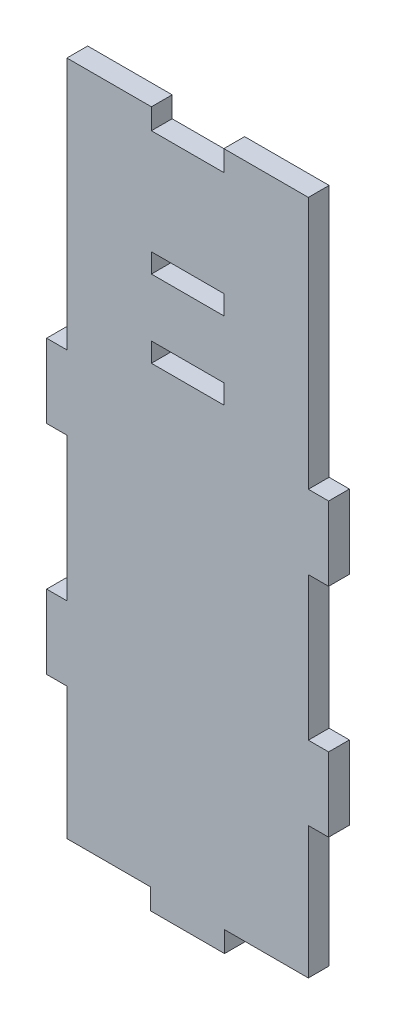
SolidWorks part; units mm, degrees
ref_plane "Front Plane" through (0, 0, 0) normal (0, 0, 1) x (1, 0, 0)
ref_plane "Top Plane" through (0, 0, 0) normal (0, 1, 0) x (1, 0, 0)
ref_plane "Right Plane" through (0, 0, 0) normal (1, 0, 0) x (0, 0, -1)
sketch "Sketch1" plane through (0, 0, 0) normal (0, 0, 1) x (1, 0, 0)
  line L0 (25, -27.35) -> (25, 2.35)
  line L1 (-25, -70) -> (-7.65, -70)
  line L2 (-25, -70) -> (-25, -42.65)
  line L3 (-25, 70) -> (-7.5, 70)
  line L4 (25, -70) -> (25, -42.65)
  line L5 (-25, -70) -> (25, 70) construction
  line L6 (-25, 70) -> (25, -70) construction
  line L7 (25, -42.65) -> (29.2, -42.65)
  line L9 (25, -27.35) -> (29.2, -27.35)
  line L10 (29.2, -42.65) -> (29.2, -27.35)
  line L11 (25, 2.35) -> (29.2, 2.35)
  line L13 (25, 17.65) -> (29.2, 17.65)
  line L14 (29.2, 2.35) -> (29.2, 17.65)
  line L15 (25, 17.65) -> (25, 70)
  line L16 (0, 65.7) -> (0, -74.3) construction
  line L17 (-29.2, 2.35) -> (-29.2, 17.65)
  line L18 (-25, 17.65) -> (-29.2, 17.65)
  line L19 (-25, 2.35) -> (-29.2, 2.35)
  line L20 (-29.2, -42.65) -> (-29.2, -27.35)
  line L21 (-25, -27.35) -> (-29.2, -27.35)
  line L22 (-25, -42.65) -> (-29.2, -42.65)
  line L23 (-25, 17.65) -> (-25, 70)
  line L24 (-25, -27.35) -> (-25, 2.35)
  line L25 (7.5, 70) -> (25, 70)
  line L27 (-7.5, 70) -> (-7.5, 65.7)
  line L28 (-7.5, 65.7) -> (7.5, 65.7)
  line L29 (7.5, 70) -> (7.5, 65.7)
  line L30 (7.65, -70) -> (25, -70)
  line L32 (-7.65, -70) -> (-7.65, -74.3)
  line L33 (-7.65, -74.3) -> (7.65, -74.3)
  line L34 (7.65, -70) -> (7.65, -74.3)
  line L36 (-7.5, 24) -> (7.5, 24)
  line L37 (-7.5, 24) -> (-7.5, 28)
  line L38 (-7.5, 28) -> (7.5, 28)
  line L39 (7.5, 24) -> (7.5, 28)
  line L40 (-7.5, 24) -> (7.5, 28) construction
  line L41 (-7.5, 28) -> (7.5, 24) construction
  line L42 (-7.5, 44) -> (7.5, 44)
  line L43 (-7.5, 44) -> (-7.5, 40)
  line L44 (-7.5, 40) -> (7.5, 40)
  line L45 (7.5, 44) -> (7.5, 40)
  line L46 (-7.5, 44) -> (7.5, 40) construction
  line L47 (-7.5, 40) -> (7.5, 44) construction
  point P0 (0, 0)
  point P16 (29.2, -35)
  point P17 (29.2, 10)
  point P30 (0, -74.3)
  point P31 (0, 42)
  point P32 (0, 65.7)
  point P40 (0, 26)
  dimension "D1" = 50
  dimension "D2" = 140
  dimension "D3" = 4.2
  dimension "D4" = 15.3
  dimension "D5" = 15.3
  dimension "D6" = 35
  dimension "D7" = 80
  dimension "D8" = 25
  dimension "D9" = 4.3
  dimension "D10" = 15
  dimension "D11" = 25
  dimension "D12" = 15.3
  dimension "D13" = 4.3
  dimension "D14" = 42
  dimension "D15" = 4
  dimension "D16" = 15
  dimension "D17" = 26
  dimension "D18" = 15
  dimension "D19" = 4
extrude "Boss-Extrude1" add sketch "Sketch1" along normal blind 4.3
